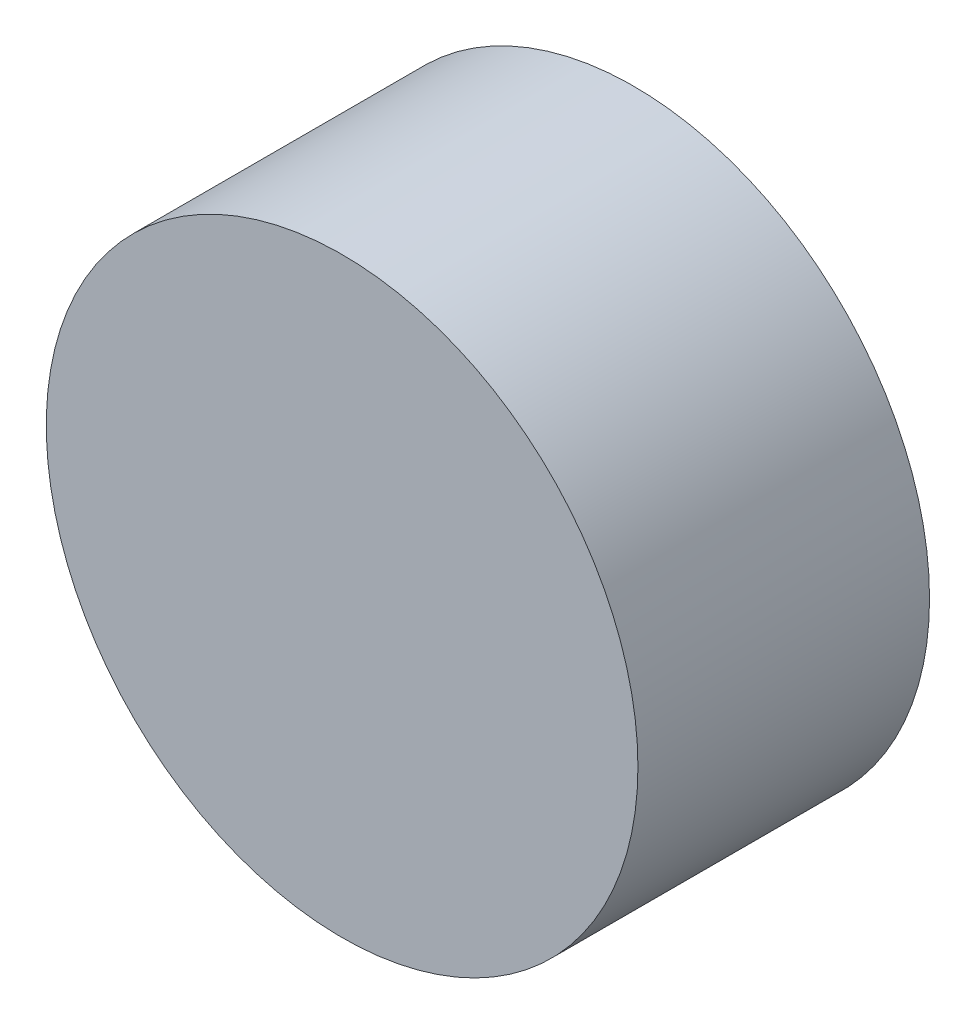
SolidWorks part; units mm, degrees
ref_plane "Plan de face" through (0, 0, 0) normal (0, 0, 1) x (1, 0, 0)
ref_plane "Plan de dessus" through (0, 0, 0) normal (0, 1, 0) x (1, 0, 0)
ref_plane "Plan de droite" through (0, 0, 0) normal (1, 0, 0) x (0, 0, -1)
sketch "Esquisse1" plane through (0, 0, 0) normal (0, 0, 1) x (1, 0, 0)
  circle A0 centre (0, 0) radius 1.4
  dimension "D1" = 2.8
extrude "Boss.-Extru.1" add sketch "Esquisse1" along normal blind 1.38
